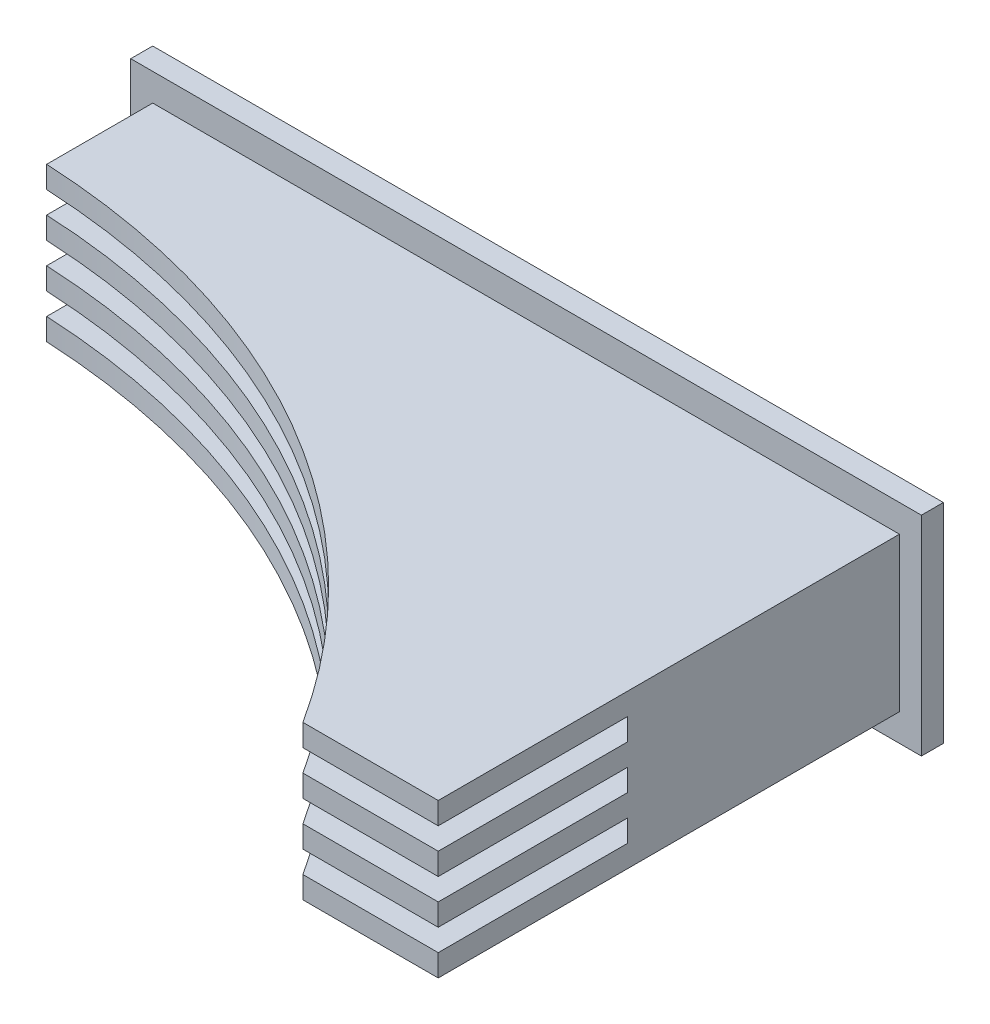
SolidWorks part; units mm, degrees
material "6061 Alloy"
ref_plane "Front Plane" through (0, 0, 0) normal (0, 0, 1) x (1, 0, 0)
ref_plane "Top Plane" through (0, 0, 0) normal (0, 1, 0) x (1, 0, 0)
ref_plane "Right Plane" through (0, 0, 0) normal (1, 0, 0) x (0, 0, -1)
other "Configuration Table"
sketch "Sketch1" plane through (0, 0, 0) normal (0, 0, 1) x (1, 0, 0)
  line L0 (-16, 6) -> (-18, 6)
  line L1 (16, 6) -> (18, 6)
  line L16 (18, 6) -> (18, 15.5)
  line L17 (18, 15.5) -> (-18, 15.5)
  line L18 (-18, 15.5) -> (-18, 6)
  line L21 (-16, 6) -> (16, 6)
sketch "Sketch2" plane through (0, 0, 0) normal (0, 0, 1) x (1, 0, 0)
  line L0 (-16, 6) -> (16, 6) construction
  line L1 (-17, 14.25) -> (17, 14.25)
  line L2 (-17, 14.25) -> (-17, 13.25)
  line L3 (-17, 13.25) -> (17, 13.25)
  line L4 (17, 14.25) -> (17, 13.25)
  line L5 (-17, 12.25) -> (17, 12.25)
  line L6 (-17, 12.25) -> (-17, 11.25)
  line L7 (-17, 11.25) -> (17, 11.25)
  line L8 (17, 12.25) -> (17, 11.25)
  line L9 (-17, 10.25) -> (17, 10.25)
  line L10 (-17, 10.25) -> (-17, 9.25)
  line L11 (-17, 9.25) -> (17, 9.25)
  line L12 (17, 10.25) -> (17, 9.25)
  line L13 (-17, 8.25) -> (17, 8.25)
  line L14 (-17, 8.25) -> (-17, 7.25)
  line L15 (-17, 7.25) -> (17, 7.25)
  line L16 (17, 8.25) -> (17, 7.25)
  line L17 (18, 6) -> (18, 15.5) construction
  line L18 (-18, 15.5) -> (-18, 6) construction
  dimension "D1" = 1
  dimension "D2" = 1
  dimension "D3" = 1
  dimension "D4" = 1
  dimension "D5" = 1.25
  dimension "D6" = 1
  dimension "D7" = 1
extrude "Extrude1" add sketch "Sketch2" along normal blind 22
sketch "Sketch3" plane through (0, 14.25, 0) normal (0, 1, 0) x (1, 0, 0)
  line L1 (17, -22) -> (-17, -22) construction
  line L2 (-17, -22) -> (-17, 0) construction
  arc A0 (-17, -5.8298) -> (10.8391, -22) centre (-18.721, -40.8421) cw
extrude "Cut-Extrude1" cut sketch "Sketch3" against normal through all and the other way through all flip side to cut
extrude "Extrude2" add sketch "Sketch1" along normal blind 1
sketch "Sketch4" plane through (0, 14.25, 0) normal (0, 1, 0) x (1, 0, 0)
  line L0 (17, -22) -> (17, -1) construction
  line L1 (17, -1) -> (-17, -1) construction
  line L2 (17, -13.3844) -> (17, -1)
  line L3 (17, -1) -> (2.3152, -1)
  arc A2 (19.2716, -16.6249) -> (-16.509, 4.1581) centre (-18.721, -40.8421) ccw
  arc A3 (17, -13.3844) -> (2.3152, -1) centre (-18.721, -40.8421) ccw
  dimension "D1" = 10
extrude "Extrude3" add sketch "Sketch4" against normal up to surface (7 mm away) up to face at (2.561, 7.25, 9.689)
